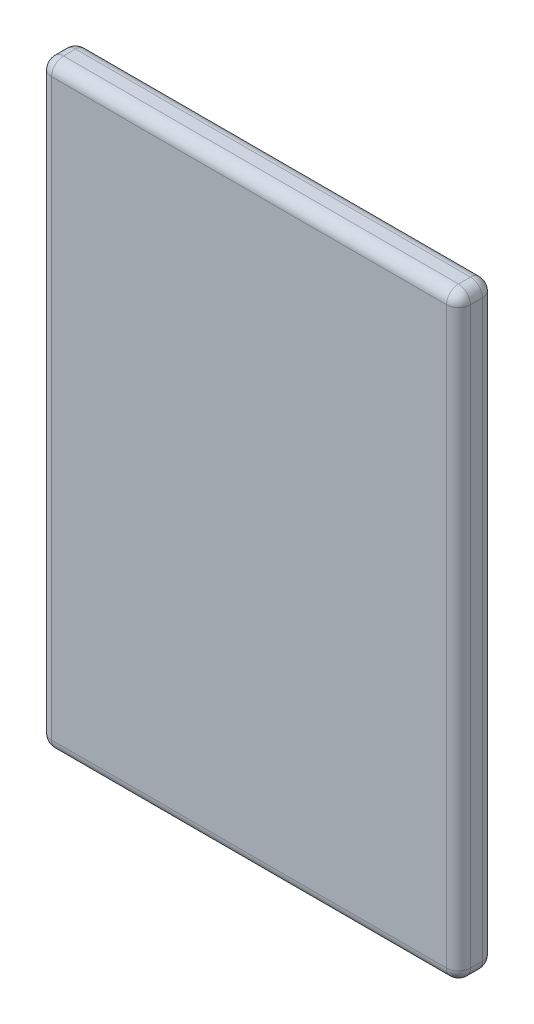
SolidWorks part; units mm, degrees
ref_plane "Front Plane" through (0, 0, 0) normal (0, 0, 1) x (1, 0, 0)
ref_plane "Top Plane" through (0, 0, 0) normal (0, 1, 0) x (1, 0, 0)
ref_plane "Right Plane" through (0, 0, 0) normal (1, 0, 0) x (0, 0, -1)
sketch "Sketch2" plane through (0, 0, 0) normal (0, 0, 1) x (1, 0, 0)
  line L1 (0, 0) -> (70, 0)
  line L2 (0, 0) -> (0, 100)
  line L3 (0, 100) -> (70, 100)
  line L4 (70, 0) -> (70, 100)
  dimension "D1" = 100
  dimension "D2" = 70
extrude "Boss-Extrude1" add sketch "Sketch2" along normal blind 6
fillet "Fillet1" radius 2 12 edges at (0, 0, 3) (0, 100, 3) (70, 0, 3) (70, 100, 3) (35, 0, 0) (70, 50, 0) (35, 100, 0) (0, 50, 0) (35, 100, 6) (70, 50, 6) (35, 0, 6) (0, 50, 6)
